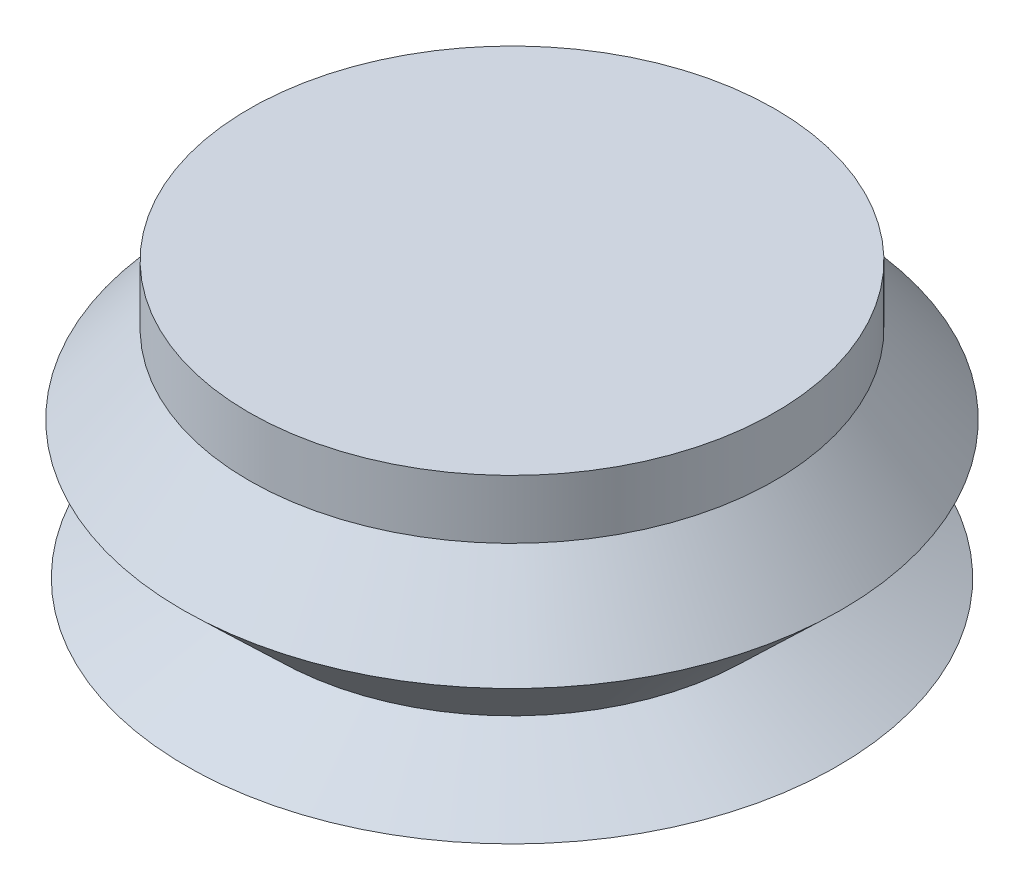
SolidWorks part; units mm, degrees
ref_plane "前视基准面" through (0, 0, 0) normal (0, 0, 1) x (1, 0, 0)
ref_plane "上视基准面" through (0, 0, 0) normal (0, 1, 0) x (1, 0, 0)
ref_plane "右视基准面" through (0, 0, 0) normal (1, 0, 0) x (0, 0, -1)
sketch "草图1" plane through (0, 0, 0) normal (0, 0, 1) x (1, 0, 0)
  line L0 (0, 0) -> (0, 35)
  line L1 (0, 0) -> (41.5, 0)
  line L2 (41.5, 0) -> (30, 6)
  line L3 (30, 6) -> (42, 17.5)
  line L4 (42, 17.5) -> (0, 17.5) construction
  line L5 (42, 17.5) -> (33.5, 27.5)
  line L6 (33.5, 27.5) -> (33.5, 35)
  line L7 (33.5, 35) -> (0, 35)
  dimension "D1" = 41.5
  dimension "D2" = 42
  dimension "D3" = 35
  dimension "D4" = 17.5
  dimension "D5" = 6
  dimension "D6" = 30
  dimension "D7" = 27.5
  dimension "D8" = 33.5
revolve "旋转1" add sketch "草图1" angle 360 about L0
